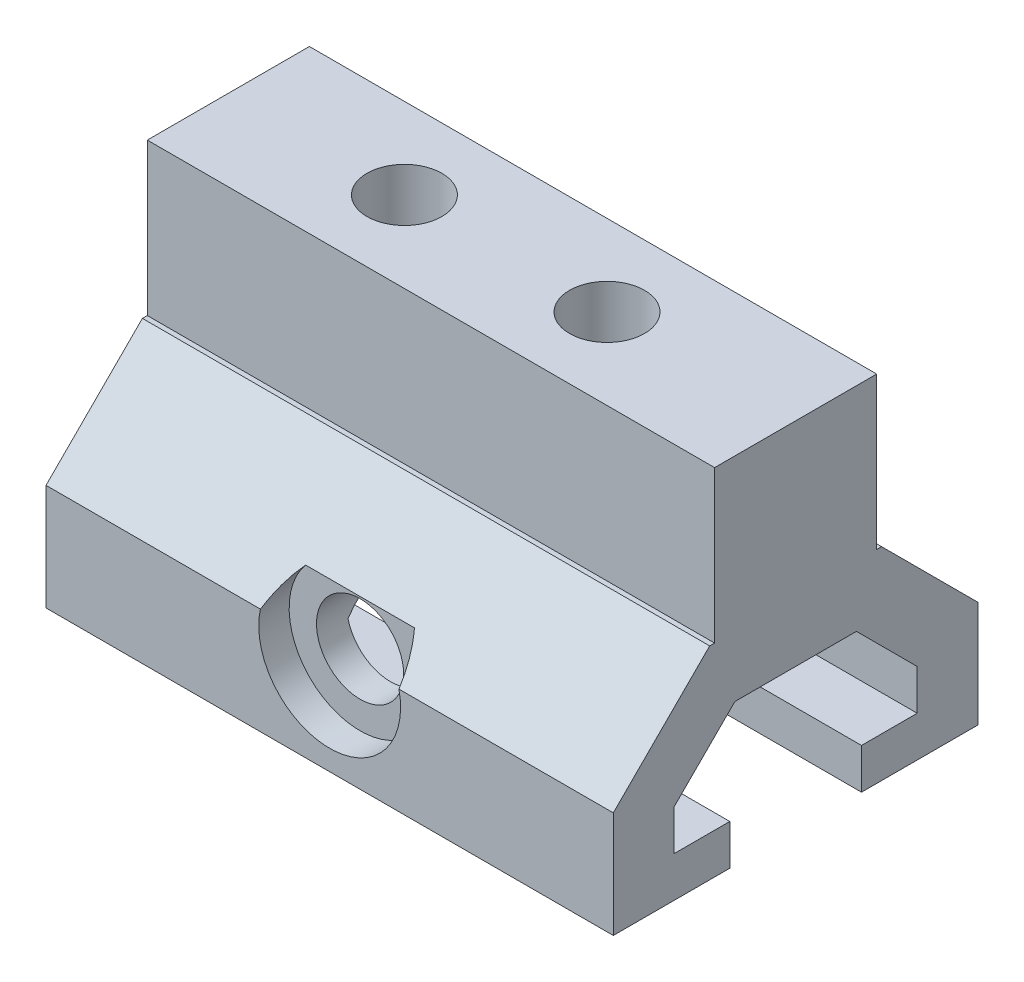
SolidWorks part; units mm, degrees
ref_plane "Alzado" through (0, 0, 0) normal (0, 0, 1) x (1, 0, 0)
ref_plane "Planta" through (0, 0, 0) normal (0, 1, 0) x (1, 0, 0)
ref_plane "Vista lateral" through (0, 0, 0) normal (1, 0, 0) x (0, 0, -1)
sketch "Croquis1" plane through (0, 0, 0) normal (0, 1, 0) x (1, 0, 0)
  line L0 (-5.31, 0) -> (4.69, 0) construction
  line L1 (-14, 4) -> (14, 4)
  line L2 (-14, 4) -> (-14, -4)
  line L3 (-14, -4) -> (14, -4)
  line L4 (14, 4) -> (14, -4)
  line L5 (-14, 4) -> (14, -4) construction
  line L6 (-14, -4) -> (14, 4) construction
  line L7 (0, 0) -> (4.69, 0) construction
  circle A0 centre (-5.31, 0) radius 1.85
  circle A1 centre (4.69, 0) radius 1.85
  point P0 (0, 0)
  point P9 (0, 0)
  dimension "D2" = 3.7
  dimension "D5" = 9.31
  dimension "D1" = 10
  dimension "D3" = 28
  dimension "D4" = 8
extrude "Saliente-Extruir1" add sketch "Croquis1" along normal blind 7.5
sketch "Croquis3" plane through (-14, 0, 0) normal (-1, 0, 0) x (0, 0, 1)
  line L0 (-4.2426, 0) -> (4.2426, 0)
  line L1 (4.2426, 0) -> (9, -4.7574)
  line L2 (9, -4.7574) -> (9, -10)
  line L3 (9, -10) -> (3.25, -10)
  line L4 (3.25, -10) -> (3.25, -8)
  line L5 (3.25, -8) -> (6, -8)
  line L6 (6, -8) -> (6, -6)
  line L7 (6, -6) -> (3, -3)
  line L8 (3, -3) -> (-3, -3)
  line L9 (0, 0) -> (0, -3) construction
  line L10 (-6, -8) -> (-6, -6)
  line L11 (-4.2426, 0) -> (-9, -4.7574)
  line L12 (-9, -4.7574) -> (-9, -10)
  line L13 (-9, -10) -> (-3.25, -10)
  line L14 (-3.25, -10) -> (-3.25, -8)
  line L15 (-3.25, -8) -> (-6, -8)
  line L16 (-6, -6) -> (-3, -3)
  point P4 (0, 0)
  dimension "D1" = 5
  dimension "D2" = 2
  dimension "D3" = 3
  dimension "D4" = 3
  dimension "D5" = 6.5
  dimension "D6" = 12
  dimension "D7" = 3
  dimension "D8" = 2
  dimension "D9" = 135
  dimension "D10" = 18
  dimension "D11" = 6
extrude "Saliente-Extruir2" add sketch "Croquis3" against normal through all
sketch "Croquis4" plane through (0, 0, 0) normal (0, 1, 0) x (1, 0, 0)
  circle A1 centre (4.69, 0) radius 1.85
  circle A2 centre (4.69, 0) radius 1.85
  circle A3 centre (-5.31, 0) radius 1.85
  circle A4 centre (-5.31, 0) radius 1.85
  dimension "D1" = 0
  dimension "D2" = 0
extrude "Cortar-Extruir1" cut sketch "Croquis4" against normal through all
sketch "Croquis5" plane through (0, -3, 0) normal (0, -1, 0) x (1, 0, 0)
  circle A0 centre (-5.31, 0) radius 3
  circle A1 centre (4.69, 0) radius 3
  dimension "D1" = 6
  dimension "D2" = 6
extrude "Cortar-Extruir2" cut sketch "Croquis5" against normal blind 3.5
sketch "Croquis6" plane through (0, 0, 9) normal (0, 0, 1) x (1, 0, 0)
  line L0 (14, -8) -> (-14, -8) construction
  line L1 (14, -8) -> (-14, -8) construction
  line L3 (-5.31, -3) -> (-14, -3) construction
  line L4 (0, -3) -> (0, -5.5) construction
  line L5 (0, -5.5) -> (0, -8) construction
  line L6 (-14, -10) -> (-14, -4.7574) construction
  line L7 (-5.31, -3) -> (-14, -3) construction
  line L8 (-5.31, -3) -> (14, -3) construction
  circle A0 centre (0, -5.5) radius 1.9
  line M6 (14, -4.7574) -> (-14, -4.7574)
  dimension "D1" = 3.8
  dimension "D2" = 14
extrude "Cortar-Extruir3" cut sketch "Croquis6" against normal through all contours A0 M6 | A0 M6
sketch "Croquis7" plane through (0, 0, 9) normal (0, 0, 1) x (1, 0, 0)
  circle A0 centre (0, -5.5) radius 3.5
  dimension "D1" = 7
extrude "Cortar-Extruir4" cut sketch "Croquis7" against normal blind 1.5
sketch "Croquis8" plane through (0, 0, 7.5) normal (0, 0, 1) x (1, 0, 0)
  circle A0 centre (0, -5.5) radius 2.15
  dimension "D1" = 4.3
extrude "Cortar-Extruir5" cut sketch "Croquis8" against normal blind 5
